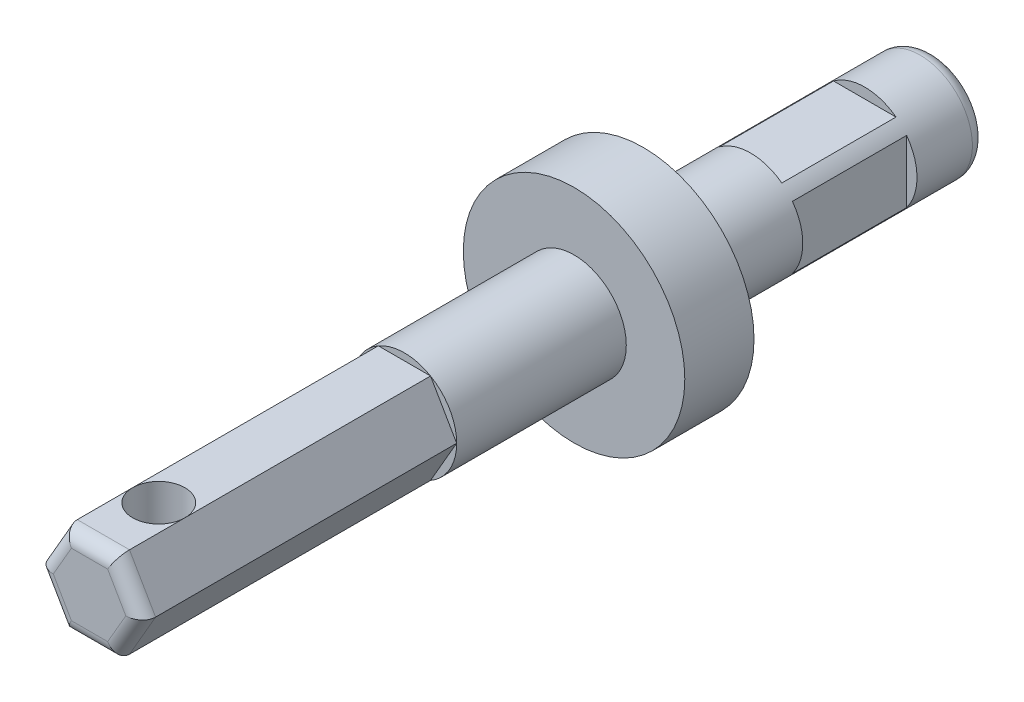
SolidWorks part; units mm, degrees
ref_plane "Front Plane" through (0, 0, 0) normal (0, 0, 1) x (1, 0, 0)
ref_plane "Top Plane" through (0, 0, 0) normal (0, 1, 0) x (1, 0, 0)
ref_plane "Right Plane" through (0, 0, 0) normal (1, 0, 0) x (0, 0, -1)
sketch "Sketch1" plane through (0, 0, 0) normal (0, 0, 1) x (1, 0, 0)
  line L0 (0, 0) -> (0, 50000) construction
  line L1 (-1000, 0) -> (3.773, 0) construction
  line L2 (-2.2577, 3.023) -> (2.2577, 3.023)
  line L3 (3.023, -2.2577) -> (3.023, 2.2577)
  line L4 (-2.565, 0.0018) -> (-0.0018, 2.565)
  line L5 (0.0018, -2.565) -> (2.565, -0.0018)
  arc A0 (-2.2577, 3.023) -> (3.023, -2.2577) centre (0, 0) ccw
  arc A1 (3.023, 2.2577) -> (2.2577, 3.023) centre (0, 0) ccw
  arc A2 (-2.565, 0.0018) -> (0.0018, -2.565) centre (0, 0) ccw
  arc A3 (2.565, -0.0018) -> (-0.0018, 2.565) centre (0, 0) ccw
  point P3 (0, 3.773)
  point P10 (0, 3.023)
  point P13 (3.023, 0)
  dimension "D1" = 7.546
  dimension "D3" = 5.13
  dimension "D2" = 0.75
  dimension "D4" = 3.63
  dimension "D5" = 45
extrude "Boss-Extrude1" add sketch "Sketch1" along normal blind 8.25
sketch "Sketch2" plane through (0, 0, 8.25) normal (0, 0, 1) x (1, 0, 0)
  circle A0 centre (0, 0) radius 3.773
extrude "Boss-Extrude2" add sketch "Sketch2" along normal blind 7.75
sketch "Sketch3" plane through (0, 0, 16) normal (0, 0, 1) x (1, 0, 0)
  line L1 (1.8865, 3.2675) -> (-1.8865, 3.2675)
  line L2 (-1.8865, 3.2675) -> (-3.773, 0)
  line L3 (-3.773, 0) -> (-1.8865, -3.2675)
  line L4 (-1.8865, -3.2675) -> (1.8865, -3.2675)
  line L5 (1.8865, -3.2675) -> (3.773, 0)
  line L6 (3.773, 0) -> (1.8865, 3.2675)
  circle A0 centre (0, 0) radius 3.2675 construction
extrude "Boss-Extrude3" add sketch "Sketch3" along normal blind 30
sketch "Sketch4" plane through (0, 0, 8.25) normal (0, 0, -1) x (-1, 0, 0)
  line L2 (-2.565, -0.0018) -> (-0.0018, -2.565)
  line L3 (2.565, 0.0018) -> (0.0018, 2.565)
  line L4 (-2.565, -0.0018) -> (-0.0018, -2.565)
  line L5 (2.565, 0.0018) -> (0.0018, 2.565)
  arc A2 (-0.0018, -2.565) -> (2.565, 0.0018) centre (0, 0) ccw
  arc A3 (0.0018, 2.565) -> (-2.565, -0.0018) centre (0, 0) ccw
  arc A4 (-0.0018, -2.565) -> (2.565, 0.0018) centre (0, 0) ccw
  arc A5 (0.0018, 2.565) -> (-2.565, -0.0018) centre (0, 0) ccw
  dimension "D1" = 0
extrude "Boss-Extrude4" add sketch "Sketch4" along normal up to surface (8.25 mm away) up to face at (0.7557, 0.7558, 0)
sketch "Sketch6" plane through (0, 0, 16) normal (0, 0, 1) x (1, 0, 0)
  line L1 (-1.8865, 3.2675) -> (1.8865, 3.2675)
  line L3 (1.8865, 3.2675) -> (3.773, 0)
  line L5 (-3.773, 0) -> (-1.8865, 3.2675)
  line L7 (-1.8865, -3.2675) -> (-3.773, 0)
  line L9 (1.8865, -3.2675) -> (-1.8865, -3.2675)
  line L11 (3.773, 0) -> (1.8865, -3.2675)
  arc A1 (1.8865, 3.2675) -> (-1.8865, 3.2675) centre (0, 0) ccw
  arc A2 (1.8865, 3.2675) -> (-1.8865, 3.2675) centre (0, 0) ccw
  arc A3 (3.773, 0) -> (1.8865, 3.2675) centre (0, 0) ccw
  arc A4 (3.773, 0) -> (1.8865, 3.2675) centre (0, 0) ccw
  arc A5 (-1.8865, 3.2675) -> (-3.773, 0) centre (0, 0) ccw
  arc A6 (-1.8865, 3.2675) -> (-3.773, 0) centre (0, 0) ccw
  arc A7 (-3.773, 0) -> (-1.8865, -3.2675) centre (0, 0) ccw
  arc A8 (-3.773, 0) -> (-1.8865, -3.2675) centre (0, 0) ccw
  arc A9 (-1.8865, -3.2675) -> (1.8865, -3.2675) centre (0, 0) ccw
  arc A10 (-1.8865, -3.2675) -> (1.8865, -3.2675) centre (0, 0) ccw
  arc A11 (1.8865, -3.2675) -> (3.773, 0) centre (0, 0) ccw
  arc A12 (1.8865, -3.2675) -> (3.773, 0) centre (0, 0) ccw
  dimension "D1" = 0
  dimension "D2" = 0
  dimension "D3" = 0
  dimension "D4" = 0
  dimension "D5" = 0
  dimension "D6" = 0
extrude "Boss-Extrude6" add sketch "Sketch6" along normal blind 10
sketch "Sketch7" plane through (0, 0, 26) normal (0, 0, 1) x (1, 0, 0)
  circle A0 centre (0, 0) radius 3.773
extrude "Boss-Extrude7" add sketch "Sketch7" along normal blind 7.254
sketch "Sketch8" plane through (0, 0, 46) normal (0, 0, 1) x (1, 0, 0)
  line L6 (3.773, 0) -> (1.8865, 3.2675)
  line L7 (1.8865, 3.2675) -> (-1.8865, 3.2675)
  line L8 (-1.8865, 3.2675) -> (-3.773, 0)
  line L9 (-3.773, 0) -> (-1.8865, -3.2675)
  line L10 (-1.8865, -3.2675) -> (1.8865, -3.2675)
  line L11 (1.8865, -3.2675) -> (3.773, 0)
  line L12 (3.773, 0) -> (1.8865, 3.2675)
  line L13 (1.8865, 3.2675) -> (-1.8865, 3.2675)
  line L14 (-1.8865, 3.2675) -> (-3.773, 0)
  line L15 (-3.773, 0) -> (-1.8865, -3.2675)
  line L16 (-1.8865, -3.2675) -> (1.8865, -3.2675)
  line L17 (1.8865, -3.2675) -> (3.773, 0)
  dimension "D1" = 0
extrude "Boss-Extrude8" add sketch "Sketch8" along normal blind 10
sketch "Sketch9" plane through (0, 0, 0) normal (0, 0, -1) x (-1, 0, 0)
  circle A0 centre (0, 0) radius 3.773
extrude "Boss-Extrude9" add sketch "Sketch9" along normal blind 5
fillet "Fillet1" radius 1 1 edges at (-3.773, 0, -5)
ref_plane "Plane1" through (0, 0, 16) normal (0, 0, 1) x (1, 0, 0)
sketch "Sketch10" plane through (0, 0, 16) normal (0, 0, 1) x (1, 0, 0)
  circle A0 centre (0, 0) radius 8
  dimension "D1" = 16
extrude "Boss-Extrude10" add sketch "Sketch10" along normal blind 5
sketch "Sketch11" plane through (0, 3.2675, 0) normal (0, 1, 0) x (1, 0, 0)
  line L0 (1.8865, -56) -> (-1.8865, -56) construction
  circle A0 centre (0, -51) radius 1.8865
  dimension "D1" = 5
  dimension "D2" = 3.773
extrude "Cut-Extrude1" cut sketch "Sketch11" against normal through all
fillet "Fillet2" radius 1 6 edges at (2.8297, -1.6338, 56) (2.8297, 1.6338, 56) (0, 3.2675, 56) (-2.8297, 1.6338, 56) (-2.8297, -1.6338, 56) (0, -3.2675, 56)
